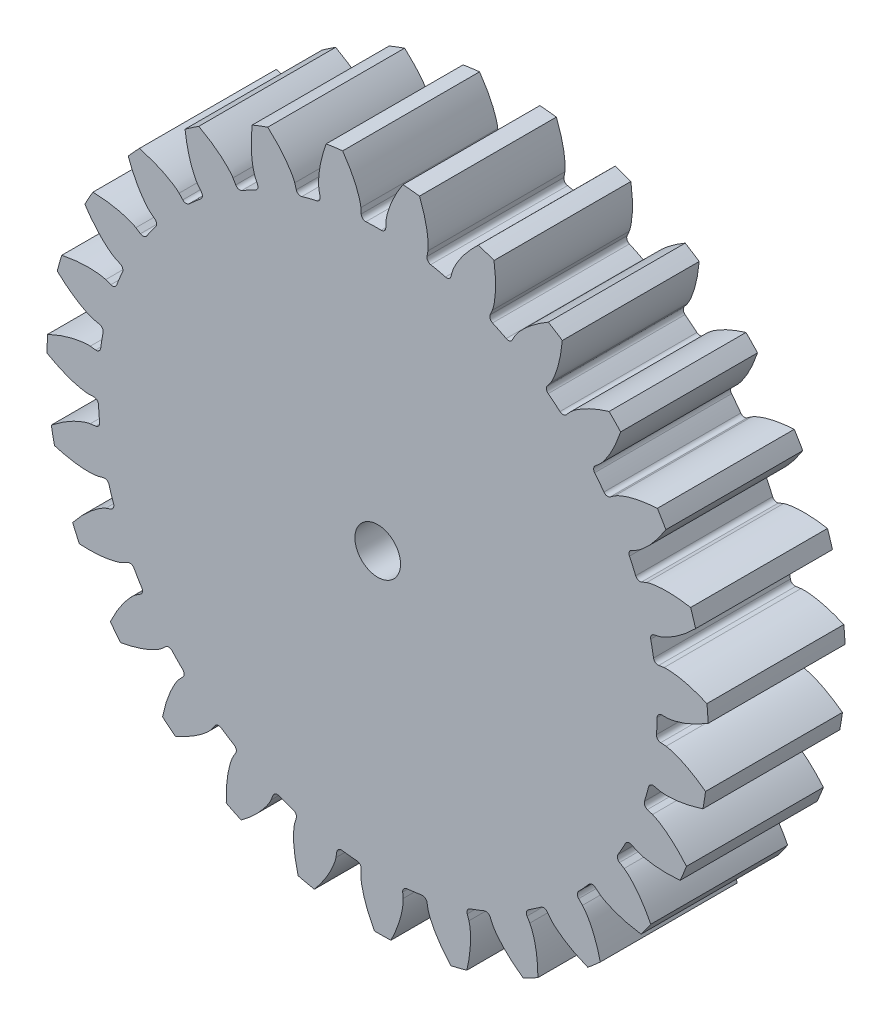
SolidWorks part; units mm, degrees
ref_plane "Front Plane" through (0, 0, 0) normal (0, 0, 1) x (1, 0, 0)
ref_plane "Top Plane" through (0, 0, 0) normal (0, 1, 0) x (1, 0, 0)
ref_plane "Right Plane" through (0, 0, 0) normal (1, 0, 0) x (0, 0, -1)
sketch "Sketch1" plane through (0, 0, 0) normal (0, 0, 1) x (1, 0, 0)
  circle A0 centre (0, 0) radius 7.25
  circle A1 centre (0, 0) radius 0.5
  dimension "D1" = 14.5
  dimension "D2" = 1
extrude "Boss-Extrude1" add sketch "Sketch1" along normal blind 3
sketch "Sketch3" plane through (0, 0, 0) normal (0, 0, 1) x (1, 0, 0)
  line L0 (6.125, 0) -> (6.3429, 0)
  line L2 (6.1021, -0.5294) -> (6.3192, -0.5483)
  line L3 (0, 0) -> (-7.2432, 0.3136) construction
  circle A0 centre (0, 0) radius 6.75 construction
  circle A1 centre (0, 0) radius 6.3429 construction
  arc A2 (6.1021, -0.5294) -> (6.125, 0) centre (0, 0) ccw
  circle A3 centre (0, 0) radius 7.25 construction
  spline S0 degree 4 poles (6.3429, 0) (6.3451, 0) (6.3512, 0.0002) (6.3699, 0.0014) (6.4069, 0.0055) (6.4523, 0.0131) (6.5043, 0.0242) (6.5542, 0.0368) (6.5967, 0.0487) (6.6389, 0.0617) (6.6808, 0.0756) (6.7313, 0.0935) (6.7915, 0.1167) (6.8614, 0.146) (6.9401, 0.1819) (7.0194, 0.2214) (7.0969, 0.2626) (7.1744, 0.3068) (7.2488, 0.3516) (7.3251, 0.4007) (7.3951, 0.4474) (7.4725, 0.5027) (7.5347, 0.5482) (7.6154, 0.6112) (7.6628, 0.6494) (7.7178, 0.6951) (7.7419, 0.716) (7.7568, 0.7288) knots 0 0 0 0 0 0.005377 0.015084 0.04661 0.092111 0.119476 0.146842 0.174209 0.201575 0.228941 0.256307 0.307035 0.361767 0.4165 0.471232 0.525964 0.580697 0.635429 0.690161 0.744894 0.799626 0.854358 0.909091 0.954545 1 1 1 1 1 construction
  spline S1 degree 4 poles (6.3429, 0) (6.3451, 0) (6.3512, 0.0002) (6.3699, 0.0014) (6.4069, 0.0055) (6.4523, 0.0131) (6.5043, 0.0242) (6.5542, 0.0368) (6.5967, 0.0487) (6.6389, 0.0617) (6.6808, 0.0756) (6.7313, 0.0935) (6.7915, 0.1167) (6.8614, 0.146) (6.9401, 0.1819) (7.0194, 0.2214) (7.0969, 0.2626) (7.1744, 0.3068) (7.2488, 0.3516) (7.3251, 0.4007) (7.3951, 0.4474) (7.4725, 0.5027) (7.5347, 0.5482) (7.5979, 0.5976) (7.6286, 0.622) (7.6442, 0.6346) knots 0 0 0 0 0 0.005377 0.015084 0.04661 0.092111 0.119476 0.146842 0.174209 0.201575 0.228941 0.256307 0.307035 0.361767 0.4165 0.471232 0.525964 0.580697 0.635429 0.690161 0.744894 0.799626 0.854358 0.909091 0.909091 0.909091 0.909091 0.909091
  spline S2 degree 4 poles (6.3192, -0.5483) (6.3213, -0.5485) (6.3274, -0.5492) (6.346, -0.552) (6.3824, -0.5593) (6.427, -0.5708) (6.4778, -0.5863) (6.5265, -0.6032) (6.5678, -0.6187) (6.6087, -0.6353) (6.6492, -0.6528) (6.698, -0.675) (6.756, -0.7033) (6.8231, -0.7385) (6.8984, -0.7811) (6.974, -0.8273) (7.0477, -0.875) (7.121, -0.9258) (7.1912, -0.9768) (7.2631, -1.0324) (7.3288, -1.085) (7.4011, -1.1467) (7.4591, -1.1974) (7.5341, -1.2672) (7.578, -1.3093) (7.6288, -1.3596) (7.6511, -1.3825) (7.6648, -1.3966) knots 0 0 0 0 0 0.005377 0.015084 0.04661 0.092111 0.119476 0.146842 0.174209 0.201575 0.228941 0.256307 0.307035 0.361767 0.4165 0.471232 0.525964 0.580697 0.635429 0.690161 0.744894 0.799626 0.854358 0.909091 0.954545 1 1 1 1 1 construction
  spline S3 degree 4 poles (6.3192, -0.5483) (6.3213, -0.5485) (6.3274, -0.5492) (6.346, -0.552) (6.3824, -0.5593) (6.427, -0.5708) (6.4778, -0.5863) (6.5265, -0.6032) (6.5678, -0.6187) (6.6087, -0.6353) (6.6492, -0.6528) (6.698, -0.675) (6.756, -0.7033) (6.8231, -0.7385) (6.8984, -0.7811) (6.974, -0.8273) (7.0477, -0.875) (7.121, -0.9258) (7.1912, -0.9768) (7.2631, -1.0324) (7.3288, -1.085) (7.4011, -1.1467) (7.4591, -1.1974) (7.5178, -1.2521) (7.5463, -1.279) (7.5607, -1.2929) knots 0 0 0 0 0 0.005377 0.015084 0.04661 0.092111 0.119476 0.146842 0.174209 0.201575 0.228941 0.256307 0.307035 0.361767 0.4165 0.471232 0.525964 0.580697 0.635429 0.690161 0.744894 0.799626 0.854358 0.909091 0.909091 0.909091 0.909091 0.909091
  point P5 (6.125, 0)
  point P11 (6.1021, -0.5294)
  dimension "D1" = 13.5
  dimension "D2" = 12.6859
  dimension "D3" = 12.25
  dimension "D4" = 2.479
  dimension "D5" = 2.479
extrude "Cut-Extrude1" cut sketch "Sketch3" against normal through all and the other way through all
fillet "Fillet1" radius 0.1 1 edges at (6.1021, -0.5294, 1.5)
fillet "Fillet2" radius 0.1 1 edges at (6.125, 0, 1.5)
pattern_circular "CirPattern14" count 27 over 360 about axis through (0, 0, 3) along (0, 0, -1) of "Cut-Extrude1", "Fillet1", "Fillet2"
equation "\"P\"= 2'Diametral Pitch"
equation "\"N\"= 27'Number of teeth"
equation "\"phi\"= 20deg'pressure angle"
equation "\"a\"= 1 / \"P\"'addendum"
equation "\"b\"= 1.25 / \"P\"'dedendum"
equation "\"c\"= \"b\" - \"a\"'clearance"
equation "\"dp\"= \"N\" / \"P\"'pitch circle diameter"
equation "\"db\"= \"dp\" * cos ( \"phi\" )'base circle diameter"
equation "\"D1@Sketch1\"= \"dp\" + 2 * \"a\"'Addendum circle diameter"
equation "\"D1@Sketch3\"= \"dp\"'pitch circle"
equation "\"D2@Sketch3\"= \"db\" 'base circle"
equation "\"D3@Sketch3\" = \"dp\" - 2 * \"b\"'dedendum circle"
equation "\"alpha\"= sqr ( \"dp\" ^ 2 - \"db\" ^ 2 ) / \"db\" * 180 / pi - \"phi\"'alpha (deg)"
equation "\"beta\"= ( 360 / ( 4 * \"N\" ) - \"alpha\" ) * 2"
equation "\"D4@Sketch3\"= 360 / ( 4 * \"N\" ) - \"alpha\""
equation "\"D5@Sketch3\"= 360 / ( 4 * \"N\" ) - \"alpha\""
